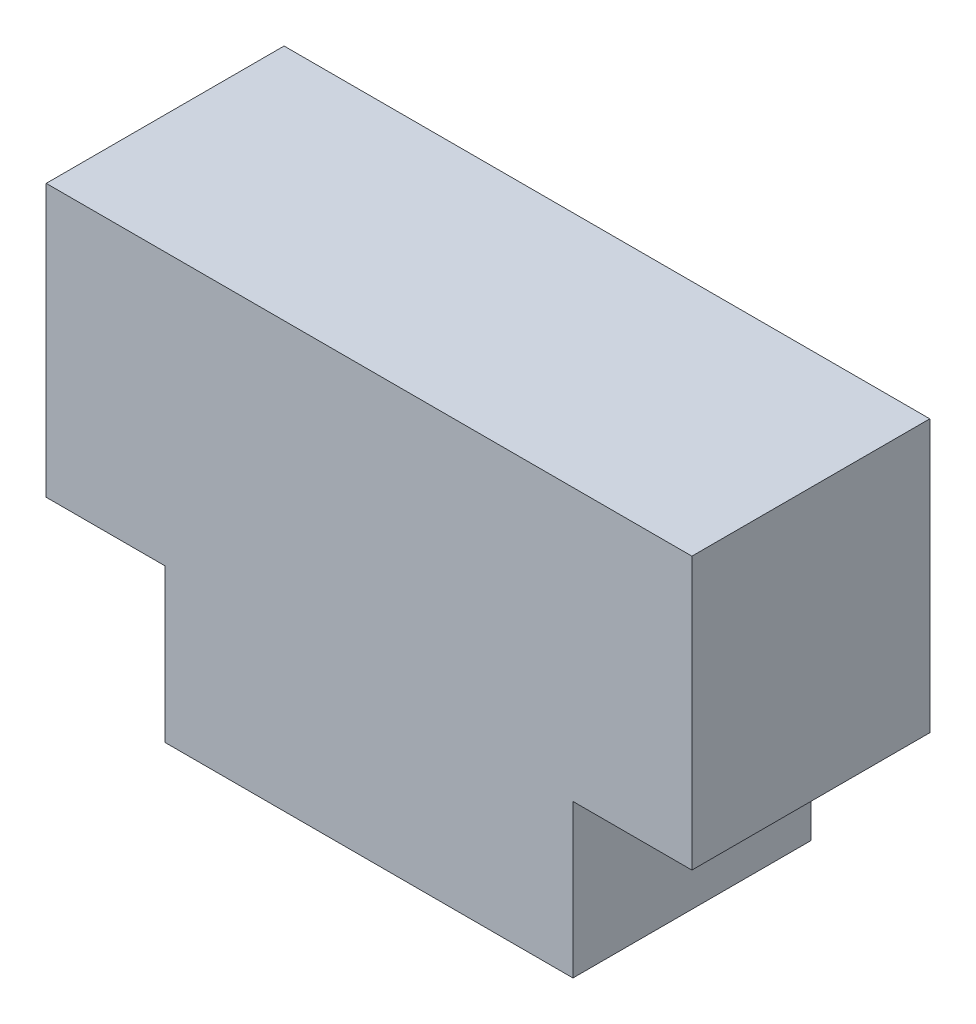
SolidWorks part; units mm, degrees
ref_plane "前视基准面" through (0, 0, 0) normal (0, 0, 1) x (1, 0, 0)
ref_plane "上视基准面" through (0, 0, 0) normal (0, 1, 0) x (1, 0, 0)
ref_plane "右视基准面" through (0, 0, 0) normal (1, 0, 0) x (0, 0, -1)
sketch "草图1" plane through (0, 0, 0) normal (0, 0, 1) x (1, 0, 0)
  line L0 (0.95, 0.4) -> (-0.95, 0.4)
  line L1 (-0.95, 0.4) -> (-0.95, -0.4)
  line L2 (-0.95, -0.4) -> (-0.6, -0.4)
  line L3 (-0.6, -0.4) -> (-0.6, -0.85)
  line L4 (-0.6, -0.85) -> (0.6, -0.85)
  line L5 (0.6, -0.85) -> (0.6, -0.4)
  line L6 (0.6, -0.4) -> (0.95, -0.4)
  line L7 (0.95, -0.4) -> (0.95, 0.4)
extrude "Component_Outline" add sketch "草图1" along normal blind 0.7 separate body
sketch3d "3D草图1"
  line L0 (0, 0, 0) -> (1, 0, 0)
  line L1 (0, 0, 0) -> (0, 1, 0)
  line L2 (0, 0, 0) -> (0, 0, 1)
  point P0 (0, 0, 0)
